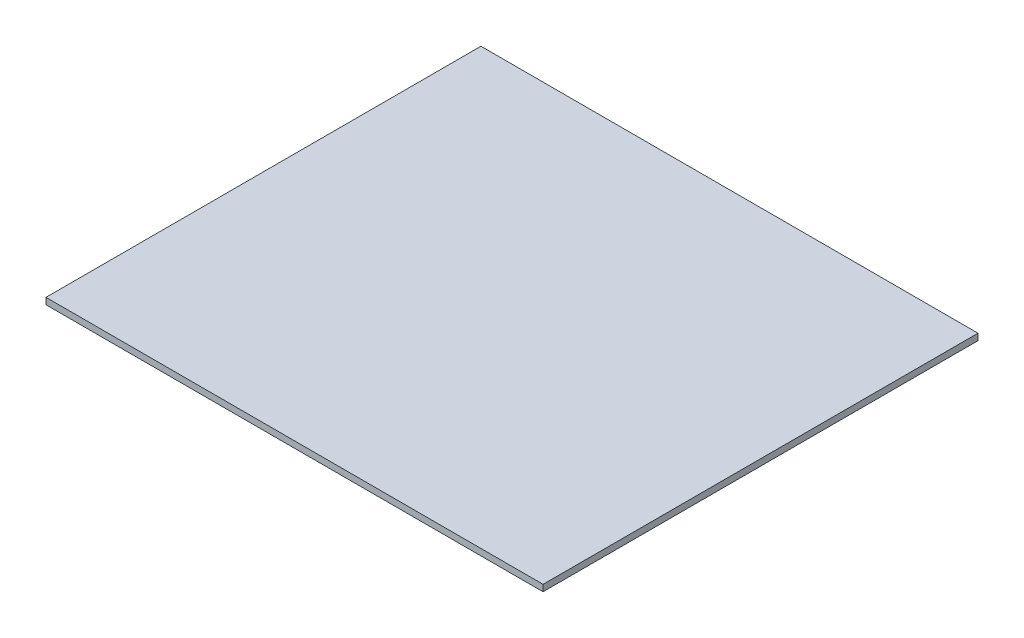
SolidWorks part; units mm, degrees
ref_plane "Płaszczyzna przednia" through (0, 0, 0) normal (0, 0, 1) x (1, 0, 0)
ref_plane "Płaszczyzna górna" through (0, 0, 0) normal (0, 1, 0) x (1, 0, 0)
ref_plane "Płaszczyzna prawa" through (0, 0, 0) normal (1, 0, 0) x (0, 0, -1)
sketch "Szkic1" plane through (0, 0, 0) normal (0, 1, 0) x (1, 0, 0)
  line L0 (-55, 0) -> (55, 0) construction
  line L1 (-715, -375) -> (715, -375)
  line L2 (-715, -375) -> (-715, 375)
  line L3 (-715, 375) -> (715, 375)
  line L4 (715, -375) -> (715, 375)
  line L6 (0, -55) -> (0, 55) construction
  point P4 (-715, 0)
  point P7 (0, 375)
  dimension "D1" = 1430
  dimension "D2" = 750
extrude "Dodanie-wyciągnięcie1" add sketch "Szkic1" along normal blind 10.4
sketch "Szkic2" [suppressed] plane through (0, 10.4, 0) normal (0, 1, 0) x (1, 0, 0)
  line L0 (715, -375) -> (715, 375) construction
  line L1 (-715, -375) -> (715, -375) construction
  line L2 (-5.72, 0) -> (5.72, 0) construction
  line L3 (0, -5.72) -> (0, 5.72) construction
  circle A0 centre (695, -355) radius 8
  circle A1 centre (695, -315) radius 8
  circle A2 centre (595, -355) radius 8
  circle A3 centre (595, -315) radius 8
  circle A4 centre (595, 315) radius 8
  circle A5 centre (595, 355) radius 8
  circle A6 centre (695, 315) radius 8
  circle A7 centre (695, 355) radius 8
  circle A8 centre (-695, 355) radius 8
  circle A9 centre (-695, 315) radius 8
  circle A10 centre (-595, 355) radius 8
  circle A11 centre (-595, 315) radius 8
  circle A12 centre (-595, -315) radius 8
  circle A13 centre (-595, -355) radius 8
  circle A14 centre (-695, -315) radius 8
  circle A15 centre (-695, -355) radius 8
  dimension "D3" = 16
  dimension "D1" = 100
  dimension "D2" = 40
  dimension "D4" = 20
  dimension "D5" = 20
extrude "Wytnij-wyciągnięcie1" [suppressed] cut sketch "Szkic2" against normal up to next
sketch "Szkic3" plane through (0, 10.4, 0) normal (0, 1, 0) x (1, 0, 0)
  line L1 (-715, -375) -> (85, -375)
  line L2 (-715, -375) -> (-715, 325)
  line L3 (-715, 325) -> (85, 325)
  line L4 (85, -375) -> (85, 325)
  line L5 (-878.942, 539.9844) -> (876.0073, 539.9844)
  line L6 (-878.942, 539.9844) -> (-878.942, -535.5824)
  line L7 (-878.942, -535.5824) -> (876.0073, -535.5824)
  line L8 (876.0073, 539.9844) -> (876.0073, -535.5824)
  dimension "D1" = 800
  dimension "D2" = 700
extrude "Wytnij-wyciągnięcie2" cut sketch "Szkic3" against normal blind 200
